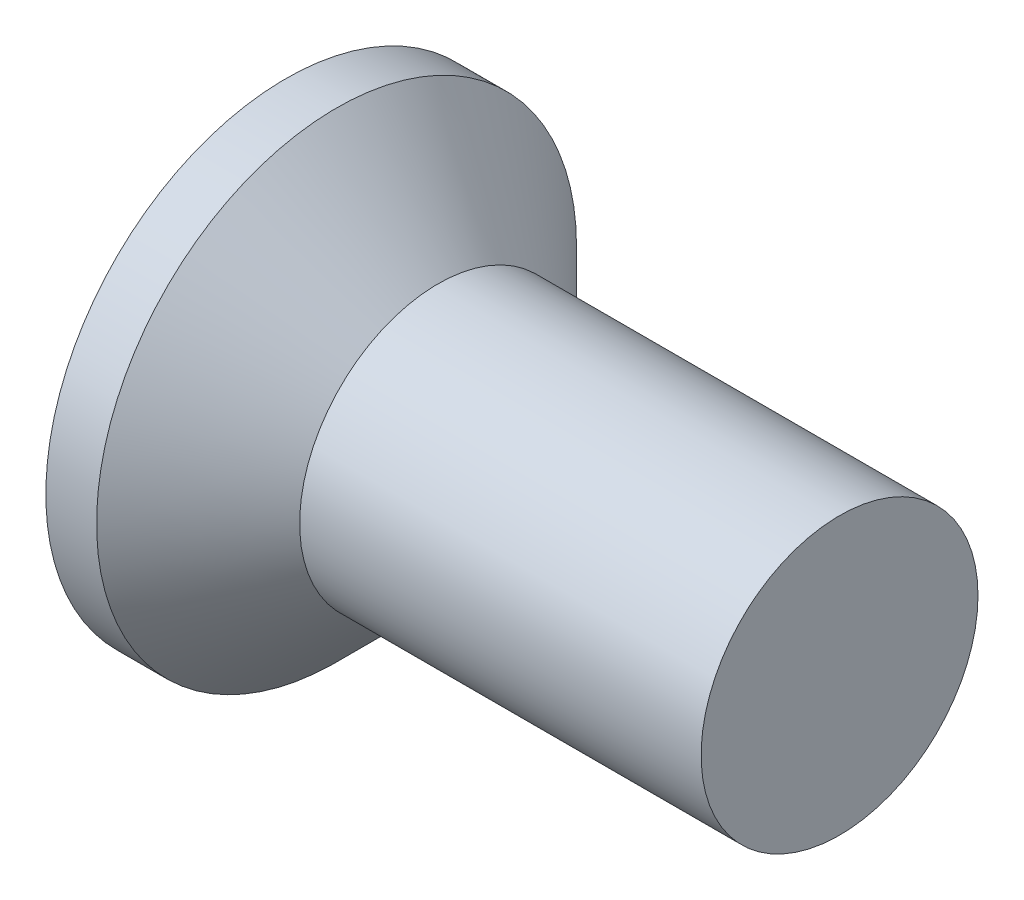
SolidWorks part; units mm, degrees
ref_plane "Front" through (0, 0, 0) normal (0, 0, 1) x (1, 0, 0)
ref_plane "Top" through (0, 0, 0) normal (0, 1, 0) x (1, 0, 0)
ref_plane "Right" through (0, 0, 0) normal (1, 0, 0) x (0, 0, -1)
sketch "Sketch1" plane through (0, 0, 0) normal (0, 0, 1) x (1, 0, 0)
  line L0 (6, 1.5) -> (2.65, 1.5)
  line L1 (2.65, 1.5) -> (1.65, 1.5)
  line L2 (1.65, 1.5) -> (0.55, 2.6)
  line L3 (0.55, 2.6) -> (0, 2.6)
  line L4 (6, 1.5) -> (6, 0)
  line L5 (4.5158, 0) -> (-89.8219, 0) construction
  line L6 (6, 0) -> (0, 0)
  line L7 (0, 2.6) -> (0, 0)
  dimension "D1" = 45
  dimension "d" = 3
  dimension "dk" = 5.2
  dimension "l" = 6
  dimension "k" = 1.65
  dimension "a" = 1
revolve "Base" add sketch "Sketch1" angle 360 about L5
cosmetic thread "ThreadCosmetic1" [suppressed] parameters "bb"=4.35, "THD_MINOR"=2.459
sketch "Sketch6" plane through (0, 0, 0) normal (1, 0, 0) x (0, 0, -1)
  line L0 (-1.9271, 0) -> (2.0512, 0) construction
  line L1 (0, 1.8651) -> (0, -2.0207) construction
  line L2 (0.32, 0.32) -> (0.32, 1.6)
  line L3 (0.32, 1.6) -> (-0.32, 1.6)
  line L4 (-0.32, 0.32) -> (-0.32, 1.6)
  line L5 (0.32, 0.32) -> (1.6, 0.32)
  line L6 (1.6, 0.32) -> (1.6, -0.32)
  line L7 (-1.6, 0.32) -> (-1.6, -0.32)
  line L8 (-0.32, 0.32) -> (-1.6, 0.32)
  line L9 (-0.32, -0.32) -> (-1.6, -0.32)
  line L10 (0.32, -0.32) -> (1.6, -0.32)
  line L11 (-0.32, -0.32) -> (-0.32, -1.6)
  line L12 (0.32, -1.6) -> (-0.32, -1.6)
  line L13 (0.32, -0.32) -> (0.32, -1.6)
  point P16 (-1.6, 0)
  point P17 (1.6, 0)
  dimension "D1" = 0.64
  dimension "m" = 3.2
extrude "CrossRecess" cut sketch "Sketch6" along normal blind 0.825
draft "Draft9" type of draft neutral plane draft angle 30 faces to draft 4 face at (0.4125, 1.6, 0) face at (0.4125, 0, 1.6) face at (0.4125, -1.6, 0) face at (0.4125, 0, -1.6) neutral plane through (0, 2.6, 0) neutral plane normal (-1, 0, 0) parameters "D1"=30
fillet "Fillet5" radius 0.3 4 edges at (0.4125, -0.32, -0.32) (0.4125, 0.32, -0.32) (0.4125, 0.32, 0.32) (0.4125, -0.32, 0.32)
sketch "Sketch7" plane through (0, 0, 0) normal (1, 0, 0) x (0, 0, -1)
  line L0 (-2.0126, 0) -> (1.9757, 0) construction
  line L1 (0, 1.9314) -> (0, -2.0126) construction
  line L2 (0, 0) -> (1.5555, 1.5555) construction
  line L3 (0, 0.4782) -> (1.1314, 1.1314)
  line L4 (-1.5402, 1.5402) -> (0, 0) construction
  line L5 (0.4782, 0) -> (1.1314, 1.1314)
  line L6 (0, -0.4782) -> (1.1314, -1.1314)
  line L7 (0.4782, 0) -> (1.1314, -1.1314)
  line L8 (-0.4782, 0) -> (-1.1314, -1.1314)
  line L9 (0, -0.4782) -> (-1.1314, -1.1314)
  line L10 (-0.4782, 0) -> (-1.1314, 1.1314)
  line L11 (0, 0.4782) -> (-1.1314, 1.1314)
  dimension "D3" = 15
extrude "Cut-Extrude3" [suppressed] cut sketch "Sketch7" along normal blind 10 draft 20
sketch "Sketch8" plane through (0, 0, 0) normal (0, 0, 1) x (1, 0, 0)
  line L0 (-19, 1.7705) -> (-20.25, 1.5)
  line L1 (-20.25, 1.5) -> (1.65, 1.5)
  line L3 (6, -1.5) -> (6, 1.5) construction
  line L6 (1.65, 1.5) -> (1.65, 6.5)
  line L7 (1.65, 6.5) -> (-19, 6.5)
  line L8 (-19, 6.5) -> (-19, 1.7705)
  line L9 (62.4753, 0.2705) -> (52.9594, 0.2705) construction
  dimension "D1" = 5
  dimension "x" = 1.25
  dimension "b" = 25
sketch "Sketch9" plane through (0, 0, 0) normal (0, 0, 1) x (1, 0, 0)
  line L0 (6, 1.2657) -> (6.1353, 1.5)
  line L1 (6.1353, 1.5) -> (6.1353, 1.7705)
  line L2 (6.1353, 1.7705) -> (5.8647, 1.7705)
  line L3 (5.8647, 1.7705) -> (5.8647, 1.5)
  line L4 (5.8647, 1.5) -> (6, 1.2657)
  line L5 (0, 0) -> (73.843, 0) construction
  line L6 (6, -1.5) -> (6, 1.5) construction
  dimension "D1" = 3
  dimension "D2" = 0.2705
revolve "Cut-Revolve10" [suppressed] cut sketch "Sketch9" angle 360 about L5
pattern_linear "LPattern10" [suppressed] count 13 spacing 0.3246 along (1, 0, 0)
equation "\"D1@Sketch6\" = \"m@Sketch6\" / 5"
equation "\"D1@CrossRecess\" = \"k@Sketch1\" / 2"
equation "\"D1@Sketch9\" = \"d@Sketch1\""
equation "\"D2@Sketch9\" =  ( \"d@Sketch1\" - \"THD_MINOR@ThreadCosmetic1\" )  / 2"
equation "\"D3@LPattern10\" = \"D2@Sketch9\" * 1.2"
equation "\"D1@LPattern10\" = \"bb@ThreadCosmetic1\" / \"D3@LPattern10\" "
